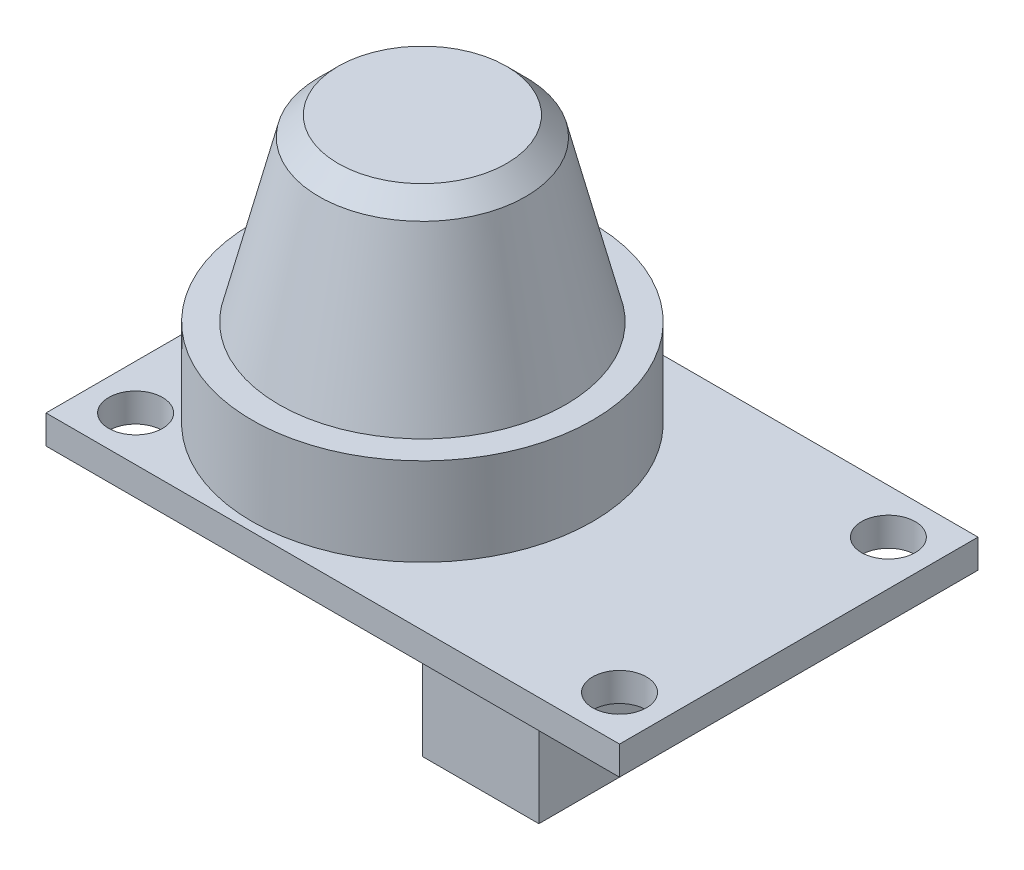
SolidWorks part; units mm, degrees
ref_plane "前视基准面" through (0, 0, 0) normal (0, 0, 1) x (1, 0, 0)
ref_plane "上视基准面" through (0, 0, 0) normal (0, 1, 0) x (1, 0, 0)
ref_plane "右视基准面" through (0, 0, 0) normal (1, 0, 0) x (0, 0, -1)
other "Configuration Table"
sketch "草图1" plane through (0, 0, 0) normal (0, 1, 0) x (1, 0, 0)
  line L1 (-16, 10) -> (16, 10)
  line L2 (-16, 10) -> (-16, -10)
  line L3 (-16, -10) -> (16, -10)
  line L4 (16, 10) -> (16, -10)
  line L5 (-16, 10) -> (16, -10) construction
  line L6 (-16, -10) -> (16, 10) construction
  circle A0 centre (-13.5, 7.5) radius 1.5
  circle A1 centre (13.5, 7.5) radius 1.5
  circle A2 centre (-13.5, -7.5) radius 1.5
  circle A3 centre (13.5, -7.5) radius 1.5
  point P0 (0, 0)
  dimension "D3" = 3
  dimension "D4" = 3
  dimension "D5" = 3
  dimension "D6" = 3
  dimension "D1" = 20
  dimension "D2" = 32
  dimension "D7" = 27
  dimension "D8" = 15
  dimension "D9" = 27
  dimension "D10" = 15
  dimension "D11" = 2.5
  dimension "D12" = 2.5
extrude "凸台-拉伸1" add sketch "草图1" along normal blind 1.6
sketch "草图2" plane through (0, 0, 0) normal (0, 1, 0) x (1, 0, 0)
  line L0 (-16, -10) -> (16, -10) construction
  line L1 (4.5, -9.5) -> (11, -9.5)
  line L2 (4.5, -9.5) -> (4.5, -3)
  line L3 (4.5, -3) -> (11, -3)
  line L4 (11, -9.5) -> (11, -3)
  line L5 (16, -10) -> (16, 10) construction
  dimension "D1" = 6.5
  dimension "D2" = 6.5
  dimension "D3" = 0.5
  dimension "D4" = 5
extrude "凸台-拉伸2" add sketch "草图2" against normal blind 5 from surface at 0 starting at face at (0, 0, 0)
sketch "草图3" plane through (0, 0, 0) normal (0, 1, 0) x (1, 0, 0)
  line L0 (-16, 10) -> (-16, -10) construction
  circle A0 centre (-5, 0) radius 9.5
  dimension "D1" = 19
  dimension "D2" = 11
extrude "凸台-拉伸3" add sketch "草图3" along normal blind 16.5
sketch "草图4" plane through (0, 0, 0) normal (0, 0, 1) x (1, 0, 0)
  line L0 (4.5, 16.5) -> (-14.5, 16.5) construction
  line L1 (4.5, 16.5) -> (-14.5, 16.5) construction
  line L2 (-5, -983.5) -> (-5, 49016.5) construction
  line L3 (0.7667, 15.4333) -> (3, 6.5)
  line L4 (3, 6.5) -> (4.5, 6.5)
  line L5 (4.5, 6.5) -> (4.5, 16.5)
  line L6 (4.5, 16.5) -> (0.5, 16.5)
  line L7 (0.7667, 15.4333) -> (-0.3, 16.5)
  line L8 (-0.3, 16.5) -> (0.5, 16.5)
  line L9 (-0.3, 16.5) -> (0.5, 16.5)
  point P2 (-5, 16.5)
  dimension "D1" = 10
  dimension "D2" = 4
  dimension "D3" = 1.5
  dimension "D4" = 0.8
  dimension "D5" = 45
  dimension "D6" = 8.9333
revolve "切除-旋转2" cut sketch "草图4" angle 360 about L2
